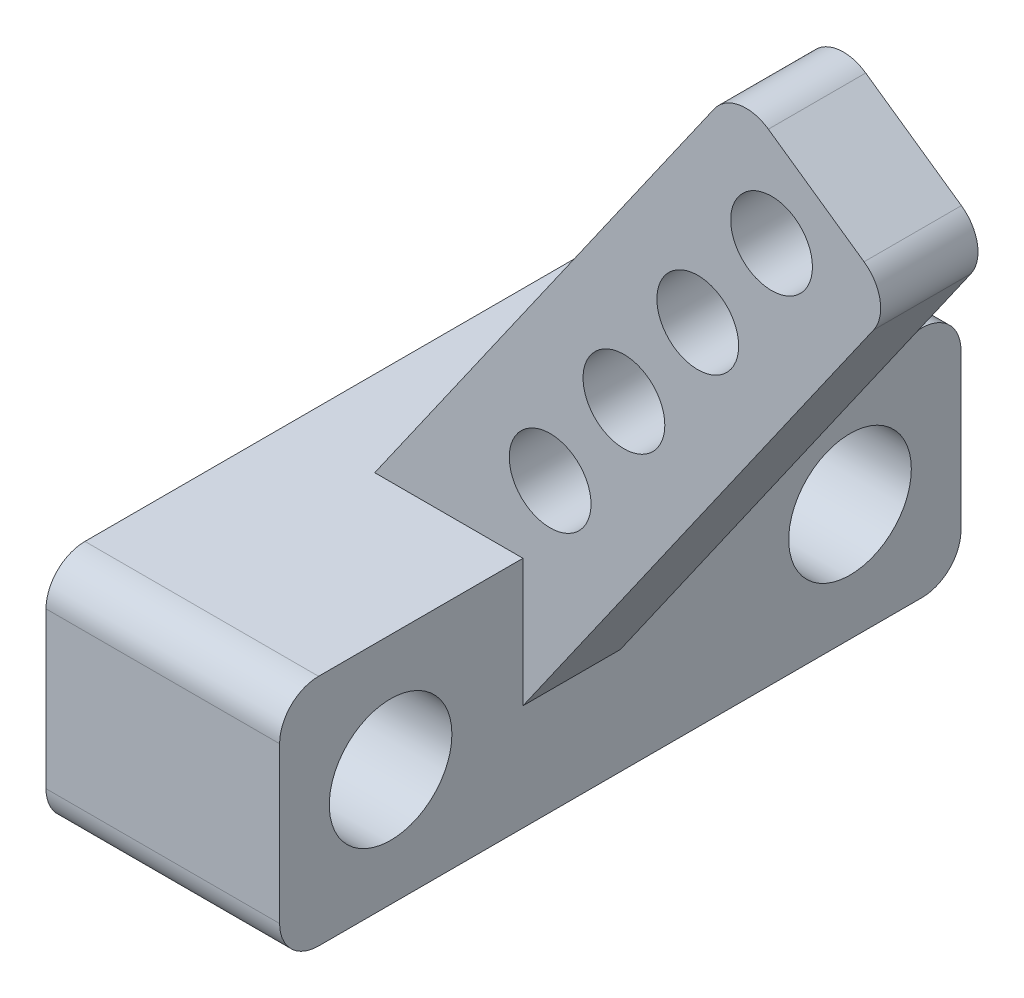
SolidWorks part; units mm, degrees
ref_plane "Front Plane" through (0, 0, 0) normal (0, 0, 1) x (1, 0, 0)
ref_plane "Top Plane" through (0, 0, 0) normal (0, 1, 0) x (1, 0, 0)
ref_plane "Right Plane" through (0, 0, 0) normal (1, 0, 0) x (0, 0, -1)
sketch "Sketch1" plane through (0, 0, 0) normal (1, 0, 0) x (0, 0, -1)
  line L0 (-11.8, 0) -> (-17.5, 0) construction
  line L1 (-15.5, -6) -> (15.5, -6)
  line L2 (-17.5, -4) -> (-17.5, 4)
  line L3 (-15.5, 6) -> (15.5, 6)
  line L4 (17.5, -4) -> (17.5, 4)
  line L5 (-17.5, -6) -> (17.5, 6) construction
  line L6 (-17.5, 6) -> (17.5, -6) construction
  line L7 (11.8, 0) -> (17.5, 0)
  circle A0 centre (-11.8, 0) radius 3.15
  circle A1 centre (11.8, 0) radius 3.15
  arc A2 (17.5, 4) -> (15.5, 6) centre (15.5, 4) ccw
  arc A3 (15.5, -6) -> (17.5, -4) centre (15.5, -4) ccw
  arc A4 (-15.5, -6) -> (-17.5, -4) centre (-15.5, -4) cw
  arc A5 (-17.5, 4) -> (-15.5, 6) centre (-15.5, 4) cw
  point P0 (0, 0)
  dimension "D3" = 6.3
  dimension "D5" = 2
  dimension "D1" = 35
  dimension "D2" = 12
  dimension "D4" = 23.6
extrude "Boss-Extrude1" add sketch "Sketch1" along normal blind 12
sketch "Sketch2" plane through (0, 0, 0) normal (0, 0, 1) x (1, 0, 0)
  line L0 (30.0128, 25.164) -> (8.1915, -6)
  line L1 (29.5217, 27.9495) -> (24.6068, 31.391)
  line L2 (8.1915, -6) -> (0, -0.2642)
  line L3 (21.8213, 30.8998) -> (0, -0.2642)
  line L4 (27.0642, 29.6702) -> (4.0958, -3.1321) construction
  line L5 (12, -4) -> (0, -4) construction
  line L6 (0, -4) -> (0, 4) construction
  line L7 (12, -6) -> (0, -6) construction
  line L8 (24.7699, 26.3936) -> (20.9786, 20.979) construction
  line L9 (20.9786, 20.979) -> (17.1872, 15.5644) construction
  line L10 (17.1872, 15.5644) -> (13.3959, 10.1498) construction
  line L12 (15.0826, 3.8415) -> (6.8911, 9.5773) construction
  circle A0 centre (24.7699, 26.3936) radius 2.1
  circle A1 centre (20.9786, 20.979) radius 2.1
  circle A2 centre (17.1872, 15.5644) radius 2.1
  circle A3 centre (13.3959, 10.1498) radius 2.1
  arc A4 (21.8213, 30.8998) -> (24.6068, 31.391) centre (23.4596, 29.7527) cw
  arc A5 (30.0128, 25.164) -> (29.5217, 27.9495) centre (28.3745, 26.3112) ccw
  point P22 (22.9685, 32.5381)
  point P29 (31.16, 26.8024)
  dimension "D4" = 4.2
  dimension "D6" = 6.61
  dimension "D9" = 2
  dimension "D1" = 55
  dimension "D2" = 10
  dimension "D3" = 4.2
  dimension "D5" = 4
  dimension "D7" = 6.61
  dimension "D8" = 6.61
extrude "Boss-Extrude2" add sketch "Sketch2" along normal blind 5
